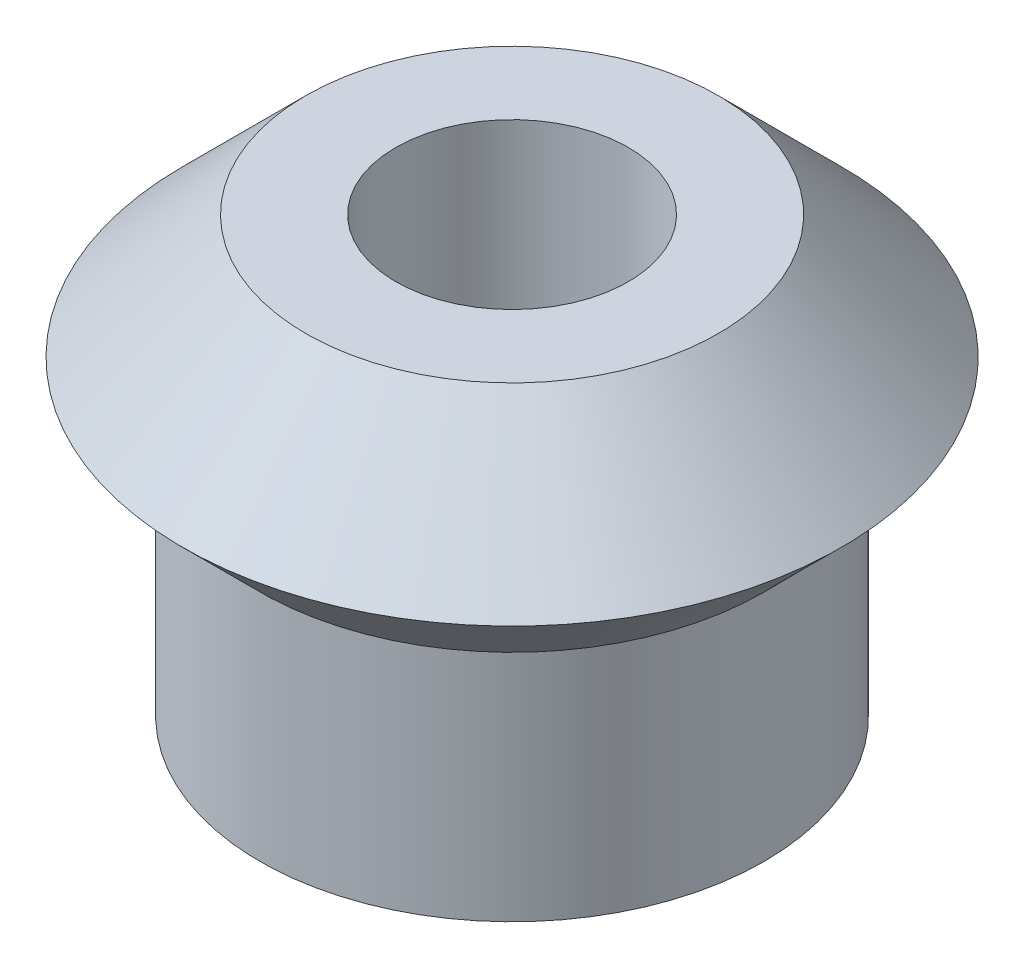
SolidWorks part; units mm, degrees
ref_plane "Plan de face" through (0, 0, 0) normal (0, 0, 1) x (1, 0, 0)
ref_plane "Plan de dessus" through (0, 0, 0) normal (0, 1, 0) x (1, 0, 0)
ref_plane "Plan de droite" through (0, 0, 0) normal (1, 0, 0) x (0, 0, -1)
sketch "Esquisse1" plane through (0, 0, 0) normal (0, 0, 1) x (1, 0, 0)
  line L0 (0, 0) -> (-6.5, 0)
  line L1 (-6.5, 0) -> (-6.5, 6.018)
  line L2 (-6.5, 6.018) -> (-8.5, 8.018)
  line L3 (-8.5, 8.018) -> (-5.318, 11.2)
  line L4 (-5.318, 11.2) -> (0, 11.2)
  line L5 (0, 11.2) -> (0, 0)
  line L6 (-5.318, 11.2) -> (0, 16.518) construction
  line L7 (0, 16.518) -> (0, 11.2) construction
  dimension "D1" = 45
  dimension "D2" = 11.2
  dimension "D3" = 4.5
  dimension "D4" = 6.5
  dimension "D5" = 8.5
revolve "Révolution1" add sketch "Esquisse1" angle 360 about L5
sketch "Esquisse2" plane through (0, 11.2, 0) normal (0, 1, 0) x (1, 0, 0)
  circle A0 centre (0, 0) radius 3
  dimension "D1" = 6
extrude "Enlèv. mat.-Extru.1" cut sketch "Esquisse2" against normal through all
